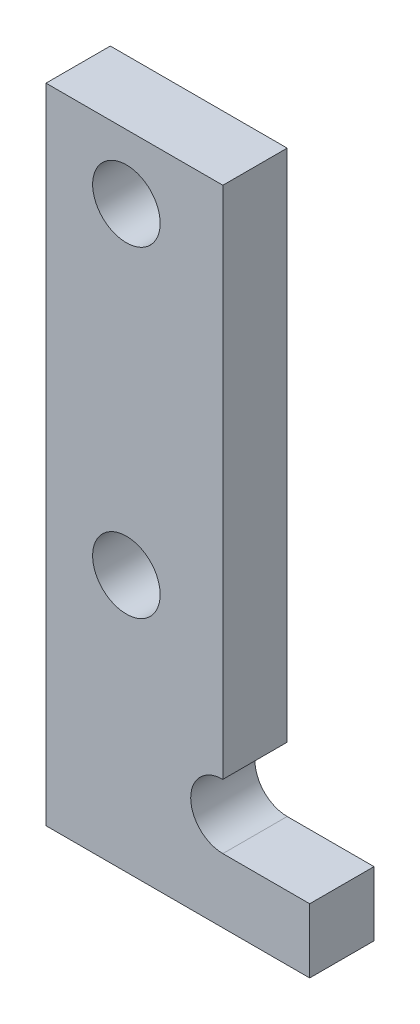
SolidWorks part; units mm, degrees
material "Thornel Mat VMA"
ref_plane "前视基准面" through (0, 0, 0) normal (0, 0, 1) x (1, 0, 0)
ref_plane "上视基准面" through (0, 0, 0) normal (0, 1, 0) x (1, 0, 0)
ref_plane "右视基准面" through (0, 0, 0) normal (1, 0, 0) x (0, 0, -1)
sketch "草图1" plane through (0, 0, 0) normal (0, 0, 1) x (1, 0, 0)
  line L1 (-2.5, -10) -> (2.5, -10)
  line L2 (-2.5, -10) -> (-2.5, 10)
  line L3 (-2.5, 10) -> (2.5, 10)
  line L4 (2.5, -10) -> (2.5, 10)
  line L5 (0, 10) -> (0, -10) construction
  line L6 (-2.5, 0) -> (2.5, 0) construction
  point P0 (0, 0)
  dimension "D1" = 5
  dimension "D2" = 20
extrude "凸台-拉伸1" add sketch "草图1" along normal blind 2
sketch "草图2" plane through (0, 0, 2) normal (0, 0, 1) x (1, 0, 0)
  line L0 (2.5, -10) -> (2.5, 10) construction
  line L1 (2.5, -8) -> (5.2, -8)
  line L2 (2.5, -8) -> (2.5, -10)
  line L3 (2.5, -10) -> (5.2, -10)
  line L4 (5.2, -8) -> (5.2, -10)
  line L5 (-2.5, -10) -> (2.5, -10) construction
  dimension "D1" = 2.7
  dimension "D2" = 2
extrude "凸台-拉伸2" add sketch "草图2" against normal up to surface (2 mm away) up to face at (0, 0, 0)
sketch "草图4" plane through (0, 0, 2) normal (0, 0, 1) x (1, 0, 0)
  line L0 (-0.5, -10) -> (-0.5, 8) construction
  line L1 (-2.5, -10) -> (5.2, -10) construction
  line L2 (2.5, -8) -> (2.5, 10) construction
  circle A0 centre (-0.5, -2) radius 1.05
  circle A1 centre (-0.5, 8) radius 1.05
  dimension "D2" = 2.1
  dimension "D1" = 3
  dimension "D3" = 8
  dimension "D4" = 10
extrude "切除-拉伸1" cut sketch "草图4" against normal blind 2
sketch "草图5" plane through (0, 0, 2) normal (0, 0, 1) x (1, 0, 0)
  line L0 (2.5, -8) -> (2.5, 10) construction
  circle A0 centre (2.5, -7) radius 1
  dimension "D1" = 2
extrude "切除-拉伸2" cut sketch "草图5" against normal blind 12
sketch "草图6" plane through (0, 0, 2) normal (0, 0, 1) x (1, 0, 0)
  line L0 (-2.5, -10) -> (5.2, -10) construction
  line L1 (-2.5, 10) -> (-3, 10)
  line L2 (-2.5, 10) -> (-2.5, -10)
  line L3 (-2.5, -10) -> (-3, -10)
  line L4 (-3, 10) -> (-3, -10)
  dimension "D1" = 0.5
extrude "凸台-拉伸3" add sketch "草图6" against normal blind 2
